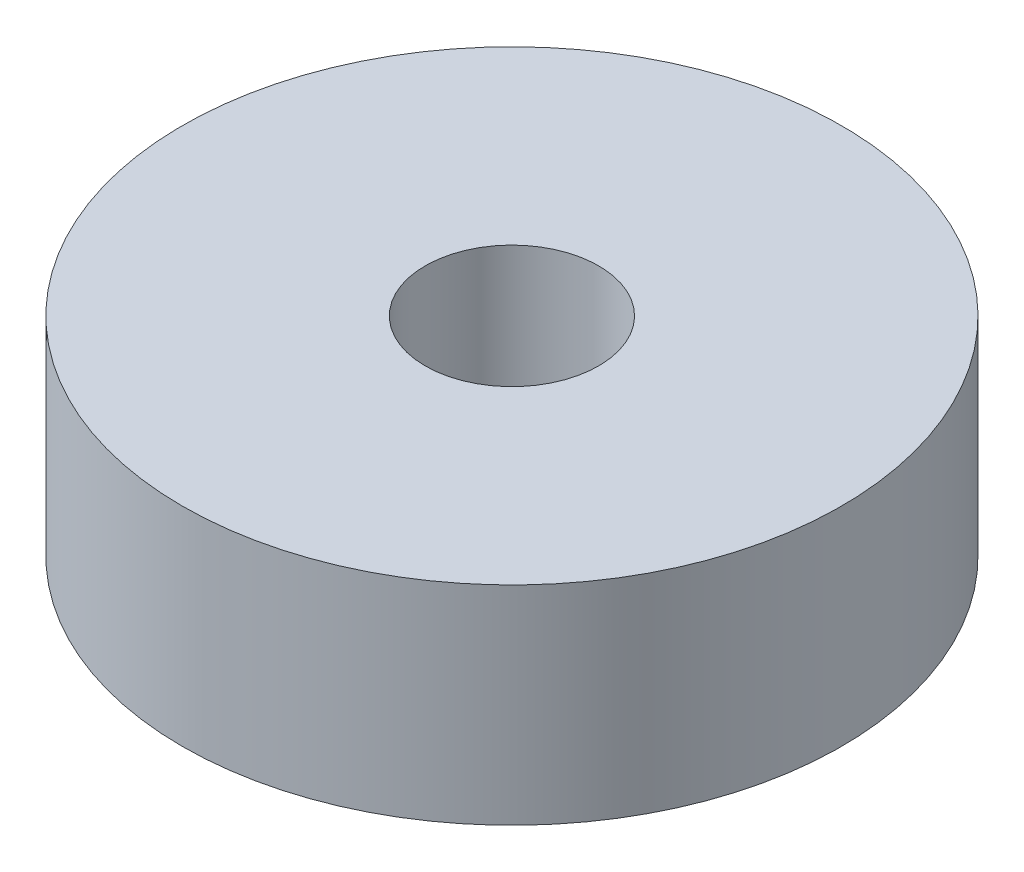
SolidWorks part; units mm, degrees
ref_plane "Płaszczyzna przednia" through (0, 0, 0) normal (0, 0, 1) x (1, 0, 0)
ref_plane "Płaszczyzna górna" through (0, 0, 0) normal (0, 1, 0) x (1, 0, 0)
ref_plane "Płaszczyzna prawa" through (0, 0, 0) normal (1, 0, 0) x (0, 0, -1)
sketch "Szkic1" plane through (0, 0, 0) normal (0, 1, 0) x (1, 0, 0)
  circle A0 centre (230.6031, -212.5374) radius 9.5
  circle A1 centre (230.6031, -212.5374) radius 2.5
  dimension "D1" = 5
  dimension "D2" = 19
extrude "Dodanie-wyciągnięcie1" add sketch "Szkic1" along normal blind 6
